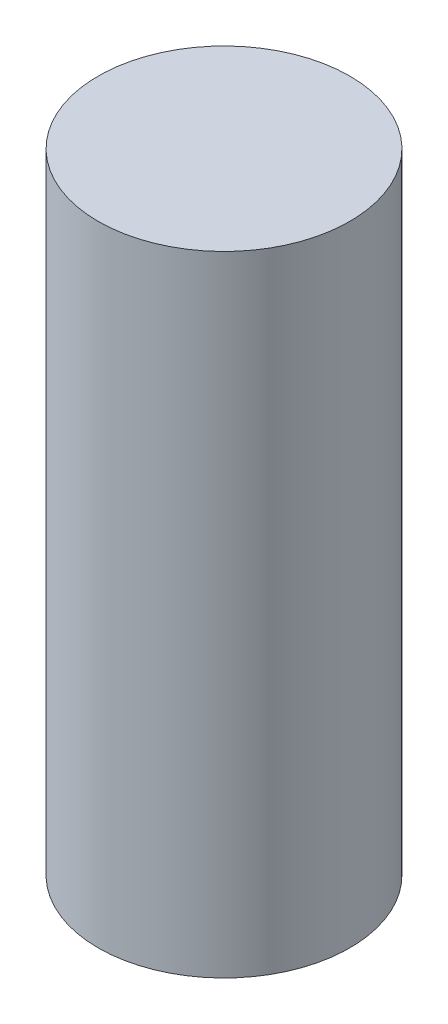
SolidWorks part; units mm, degrees
ref_plane "Front Plane" through (0, 0, 0) normal (0, 0, 1) x (1, 0, 0)
ref_plane "Top Plane" through (0, 0, 0) normal (0, 1, 0) x (1, 0, 0)
ref_plane "Right Plane" through (0, 0, 0) normal (1, 0, 0) x (0, 0, -1)
sketch "Sketch1" plane through (0, 0, 0) normal (0, 1, 0) x (1, 0, 0)
  circle A0 centre (0, 0) radius 2.5
extrude "Boss-Extrude1" add sketch "Sketch1" along normal blind 12.5
